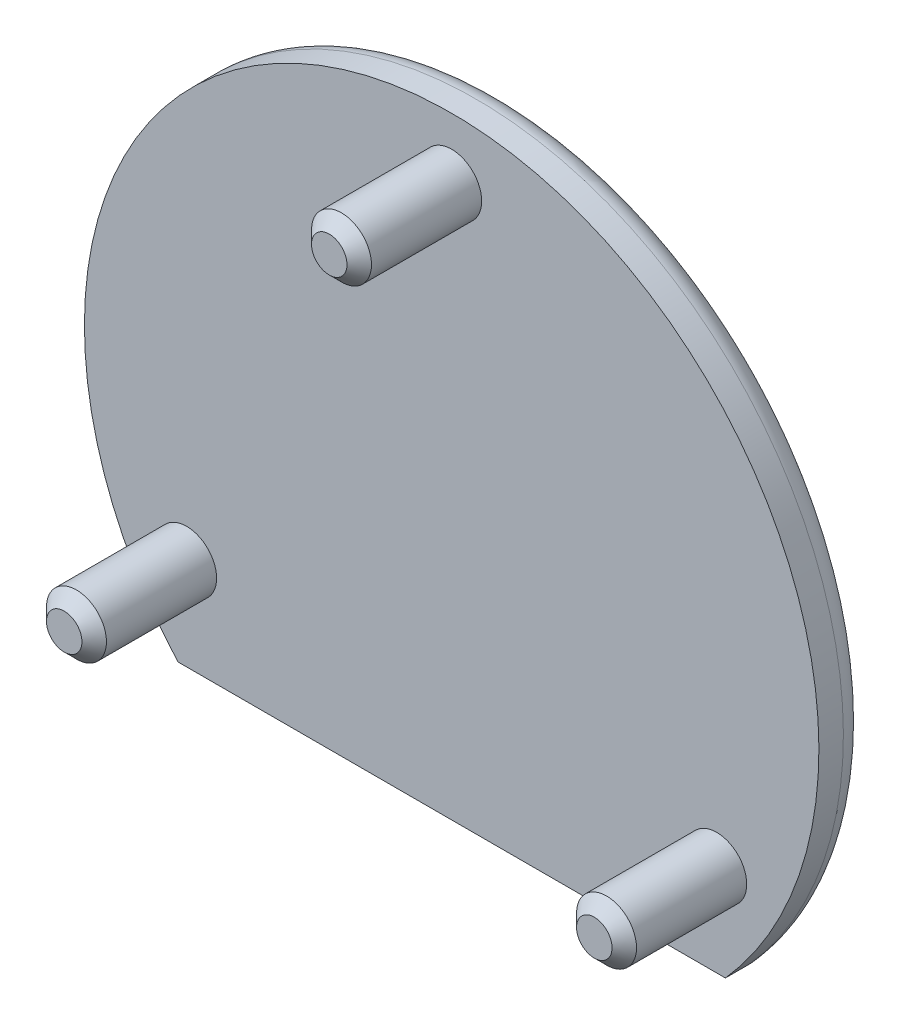
SolidWorks part; units mm, degrees
ref_plane "정면" through (0, 0, 0) normal (0, 0, 1) x (1, 0, 0)
ref_plane "윗면" through (0, 0, 0) normal (0, 1, 0) x (1, 0, 0)
ref_plane "우측면" through (0, 0, 0) normal (1, 0, 0) x (0, 0, -1)
sketch "스케치1" plane through (0, 0, 0) normal (0, 0, 1) x (1, 0, 0)
  circle A0 centre (0, 0) radius 30
  dimension "D1" = 60
extrude "보스-돌출1" add sketch "스케치1" along normal blind 4
sketch "스케치2" plane through (0, 0, 4) normal (0, 0, 1) x (1, 0, 0)
  line L0 (0, 4.9747) -> (0, -6.6631) construction
  circle A0 centre (0, 25) radius 2.45
  circle A1 centre (21.6506, -12.5) radius 2.45
  circle A2 centre (-21.6506, -12.5) radius 2.45
  point P11 (0, 0)
  dimension "D1" = 4.9
  dimension "D2" = 25
  dimension "D3" = 3
extrude "보스-돌출2" add sketch "스케치2" along normal blind 10
sketch "스케치3" plane through (0, 0, 0) normal (0, 0, -1) x (-1, 0, 0)
  line L0 (22.3607, -20) -> (-22.3607, -20)
  circle A0 centre (0, 0) radius 30 construction
  arc A1 (-22.3607, -20) -> (22.3607, -20) centre (0, 0) ccw
  dimension "D1" = 20
extrude "컷-돌출1" cut sketch "스케치3" against normal through all both and the other way through all
fillet "필렛1" radius 2 2 edges at (0, -20, 0) (0, 30, 0)
chamfer "모따기1" distance 1 angle 45 3 edges at (24.1006, -12.5, 14) (-19.2006, -12.5, 14) (2.45, 25, 14)
